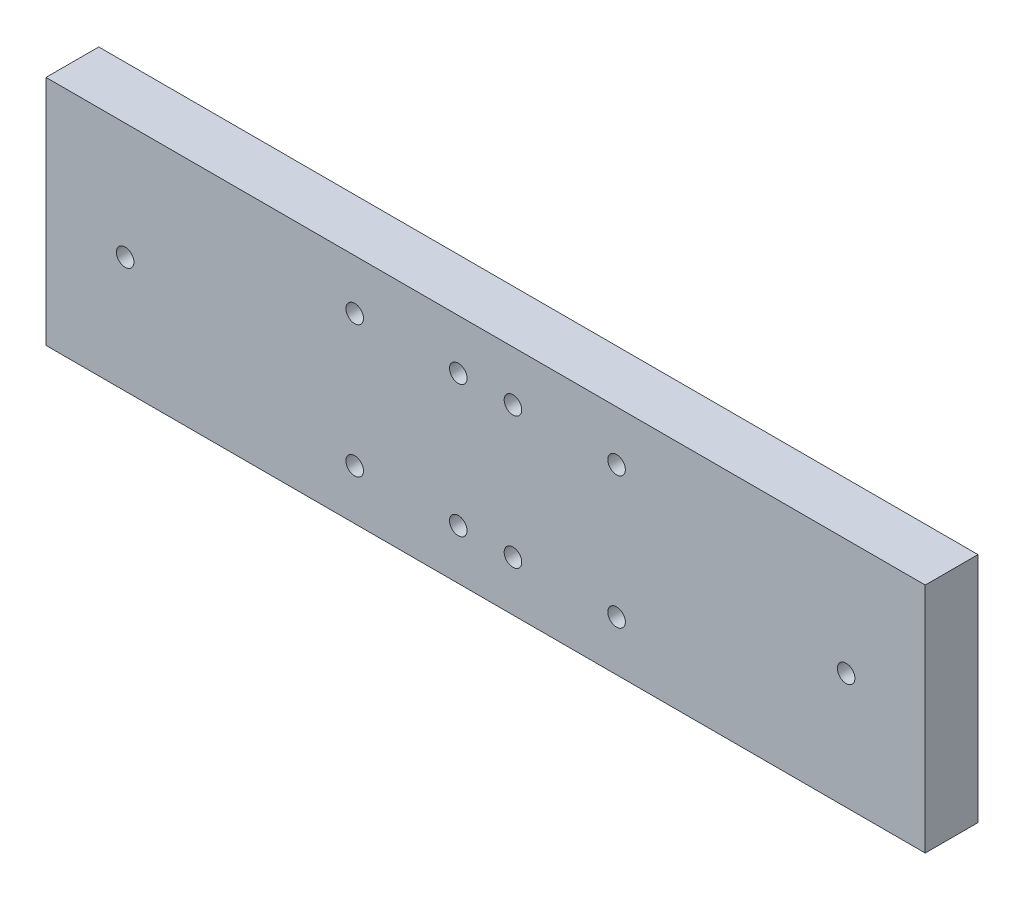
SolidWorks part; units mm, degrees
ref_plane "Front Plane" through (0, 0, 0) normal (0, 0, 1) x (1, 0, 0)
ref_plane "Top Plane" through (0, 0, 0) normal (0, 1, 0) x (1, 0, 0)
ref_plane "Right Plane" through (0, 0, 0) normal (1, 0, 0) x (0, 0, -1)
sketch "Sketch1" plane through (0, 0, 0) normal (0, 0, 1) x (1, 0, 0)
  line L0 (20, -38.75) -> (-65, -38.75) construction
  line L1 (20, -77.5) -> (20, 0) construction
  line L2 (-65, 0) -> (-65, -77.5) construction
  line L3 (102.5, -38.75) -> (80, -38.75) construction
  line L4 (102.5, -5.75) -> (-147.5, -5.75)
  line L5 (102.5, -5.75) -> (102.5, -71.75)
  line L6 (102.5, -71.75) -> (-147.5, -71.75)
  line L7 (-147.5, -5.75) -> (-147.5, -71.75)
  line L8 (102.5, -5.75) -> (-147.5, -71.75) construction
  line L9 (102.5, -71.75) -> (-147.5, -5.75) construction
  line L10 (-22.5, -5.75) -> (-22.5, -71.75) construction
  circle A0 centre (14.7287, -20) radius 2.5 construction
  circle A1 centre (14.7287, -57.5) radius 2.5 construction
  circle A2 centre (-14.7287, -57.5) radius 2.5 construction
  circle A3 centre (-14.7287, -20) radius 2.5 construction
  circle A4 centre (-30.2713, -20) radius 2.5 construction
  circle A5 centre (-30.2713, -57.5) radius 2.5 construction
  circle A6 centre (-59.7287, -57.5) radius 2.5 construction
  circle A7 centre (-59.7287, -20) radius 2.5 construction
  circle A8 centre (14.7287, -20) radius 2.5
  circle A9 centre (14.7287, -57.5) radius 2.5
  circle A10 centre (-14.7287, -57.5) radius 2.5
  circle A11 centre (-14.7287, -20) radius 2.5
  circle A12 centre (-30.2713, -20) radius 2.5
  circle A13 centre (-30.2713, -57.5) radius 2.5
  circle A14 centre (-59.7287, -57.5) radius 2.5
  circle A15 centre (-59.7287, -20) radius 2.5
  circle A16 centre (80, -38.75) radius 2.5
  circle A17 centre (-125, -38.75) radius 2.5
  point P7 (-22.5, -38.75)
  dimension "D1" = 66
  dimension "D2" = 250
  dimension "D3" = 22.5
extrude "Boss-Extrude1" add sketch "Sketch1" along normal blind 15
